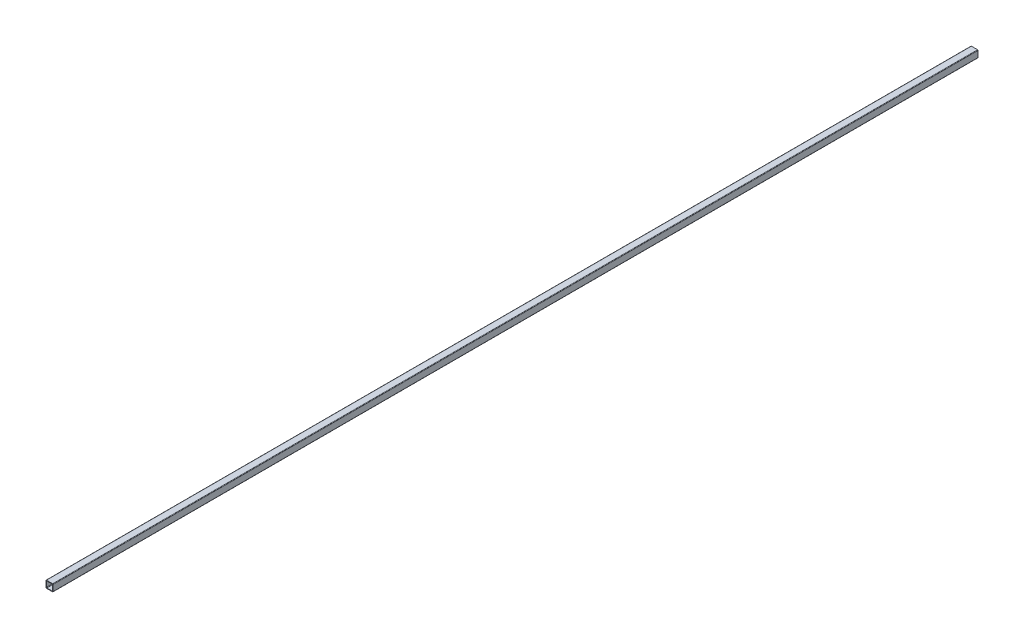
SolidWorks part; units mm, degrees
material "ASTM A500 Grade B"
ref_plane "Front Plane" through (0, 0, 0) normal (0, 0, 1) x (1, 0, 0)
ref_plane "Top Plane" through (0, 0, 0) normal (0, 1, 0) x (1, 0, 0)
ref_plane "Right Plane" through (0, 0, 0) normal (1, 0, 0) x (0, 0, -1)
sketch "Sketch1" plane through (0, 0, 0) normal (0, 0, 1) x (1, 0, 0)
  line L0 (5.3086, -2.7686) -> (32.7914, -2.7686)
  line L1 (2.54, 0) -> (35.56, 0)
  line L2 (0, -2.54) -> (0, -35.56)
  line L3 (2.54, -38.1) -> (35.56, -38.1)
  line L4 (38.1, -2.54) -> (38.1, -35.56)
  line L5 (35.3314, -5.3086) -> (35.3314, -32.7914)
  line L6 (5.3086, -35.3314) -> (32.7914, -35.3314)
  line L7 (2.7686, -5.3086) -> (2.7686, -32.7914)
  line L8 (0, 0) -> (0, -38.1) construction
  line L9 (0, -38.1) -> (38.1, -38.1) construction
  line L10 (38.1, 0) -> (38.1, -38.1) construction
  line L11 (2.7686, -2.7686) -> (2.7686, -35.3314) construction
  line L12 (2.7686, -35.3314) -> (35.3314, -35.3314) construction
  line L13 (35.3314, -2.7686) -> (35.3314, -35.3314) construction
  line L14 (2.7686, -2.7686) -> (35.3314, -2.7686) construction
  line L15 (0, 0) -> (38.1, 0) construction
  arc A0 (0, -35.56) -> (2.54, -38.1) centre (2.54, -35.56) ccw
  arc A1 (38.1, -35.56) -> (35.56, -38.1) centre (35.56, -35.56) cw
  arc A2 (2.7686, -32.7914) -> (5.3086, -35.3314) centre (5.3086, -32.7914) ccw
  arc A3 (32.7914, -35.3314) -> (35.3314, -32.7914) centre (32.7914, -32.7914) ccw
  arc A4 (35.3314, -5.3086) -> (32.7914, -2.7686) centre (32.7914, -5.3086) ccw
  arc A5 (38.1, -2.54) -> (35.56, 0) centre (35.56, -2.54) ccw
  arc A6 (0, -2.54) -> (2.54, 0) centre (2.54, -2.54) cw
  arc A7 (5.3086, -2.7686) -> (2.7686, -5.3086) centre (5.3086, -5.3086) ccw
  point P12 (0, -38.1)
  dimension "D4" = 2.54
  dimension "D3" = 2.7686
extrude "Boss-Extrude1" add sketch "Sketch1" along normal blind 5000
